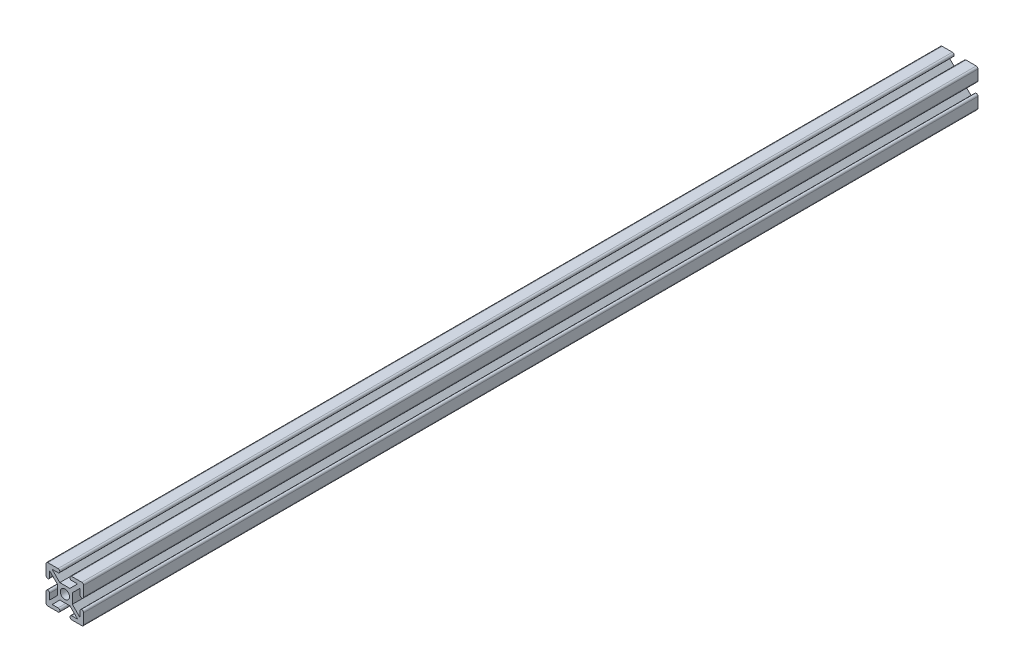
SolidWorks part; units mm, degrees
ref_plane "Front Plane" through (0, 0, 0) normal (0, 0, 1) x (1, 0, 0)
ref_plane "Top Plane" through (0, 0, 0) normal (0, 1, 0) x (1, 0, 0)
ref_plane "Right Plane" through (0, 0, 0) normal (1, 0, 0) x (0, 0, -1)
sketch "Sketch1" plane through (0, 0, 0) normal (0, 0, 1) x (1, 0, 0)
  line L0 (-19.949, 29.351) -> (-19.949, 30.776) construction
  line L1 (-0.8961, 13.201) -> (3.8289, 13.201)
  line L2 (-21.374, 38.926) -> (-21.374, 30.776)
  line L3 (-19.949, 40.351) -> (-11.799, 40.351)
  line L4 (-0.949, 40.351) -> (7.201, 40.351)
  line L5 (-16.4711, 13.201) -> (-11.7461, 13.201)
  line L6 (-12.374, 29.351) -> (-12.374, 21.351)
  line L7 (-21.3211, 19.926) -> (-21.3211, 11.776)
  line L8 (-19.9225, 10.3774) -> (-11.7461, 10.351)
  line L9 (8.626, 38.926) -> (8.626, 30.8797)
  line L10 (-18.524, 35.501) -> (-18.524, 30.776)
  line L11 (8.626, 20.0297) -> (8.626, 11.776)
  line L12 (-10.374, 38.926) -> (-11.799, 38.926) construction
  line L13 (-0.8961, 10.351) -> (7.201, 10.351)
  line L14 (-16.524, 37.501) -> (-11.799, 37.501)
  line L15 (-18.524, 19.926) -> (-18.524, 15.201)
  line L16 (-2.374, 38.926) -> (-0.949, 38.926) construction
  line L17 (-0.949, 37.501) -> (3.776, 37.501)
  line L18 (7.201, 29.4547) -> (7.201, 30.8797) construction
  line L19 (-10.374, 31.351) -> (-16.524, 37.501)
  line L20 (5.776, 35.501) -> (5.776, 30.8797)
  line L21 (7.201, 21.4547) -> (7.201, 20.0297) construction
  line L22 (-12.374, 29.351) -> (-18.524, 35.501)
  line L23 (5.776, 20.0297) -> (5.776, 15.201)
  line L24 (-2.3211, 11.776) -> (-0.8961, 11.776) construction
  line L25 (-12.374, 21.351) -> (-18.524, 15.201)
  line L26 (-10.374, 31.351) -> (-2.374, 31.351)
  line L27 (-2.374, 31.351) -> (3.776, 37.501)
  line L28 (-19.9225, 21.351) -> (-19.9225, 19.926) construction
  line L29 (-16.4711, 13.201) -> (-10.3211, 19.351)
  line L30 (-10.3211, 19.351) -> (-2.3211, 19.351)
  line L31 (-2.3211, 19.351) -> (3.8289, 13.201)
  line L32 (-10.3211, 11.776) -> (-11.7461, 11.776) construction
  line L33 (-0.374, 21.351) -> (5.776, 15.201)
  line L34 (-0.374, 29.351) -> (5.776, 35.501)
  line L35 (-0.374, 29.351) -> (-0.374, 21.351)
  circle A0 centre (-6.3211, 25.351) radius 3.645
  arc A1 (-21.374, 30.776) -> (-18.524, 30.776) centre (-19.949, 30.776) ccw
  arc A2 (-11.799, 37.501) -> (-11.799, 40.351) centre (-11.799, 38.926) ccw
  arc A3 (-0.949, 40.351) -> (-0.949, 37.501) centre (-0.949, 38.926) ccw
  arc A4 (5.776, 30.8797) -> (8.626, 30.8797) centre (7.201, 30.8797) ccw
  arc A5 (8.626, 20.0297) -> (5.776, 20.0297) centre (7.201, 20.0297) ccw
  arc A6 (-0.8961, 13.201) -> (-0.8961, 10.351) centre (-0.8961, 11.776) ccw
  arc A7 (-18.524, 19.926) -> (-21.3211, 19.926) centre (-19.9225, 19.926) ccw
  arc A8 (-11.7461, 10.351) -> (-11.7461, 13.201) centre (-11.7461, 11.776) ccw
  arc A9 (-21.3211, 11.776) -> (-19.9225, 10.3774) centre (-19.9225, 11.776) ccw
  arc A10 (7.201, 10.351) -> (8.626, 11.776) centre (7.201, 11.776) ccw
  arc A11 (8.626, 38.926) -> (7.201, 40.351) centre (7.201, 38.926) ccw
  arc A12 (-19.949, 40.351) -> (-21.374, 38.926) centre (-19.949, 38.926) ccw
  dimension "D1" = 1.425
  dimension "D2" = 1.425
  dimension "D3" = 1.425
  dimension "D4" = 1.425
  dimension "D5" = 1.425
  dimension "D6" = 1.425
  dimension "D7" = 1.425
extrude "Boss-Extrude1" add sketch "Sketch1" along normal blind 713.12
sketch "Sketch2" plane through (-0.374, 0, 0) normal (1, 0, 0) x (0, 0, -1)
  line L1 (-713.12, 21.351) -> (-713.12, 29.351) construction
  line L2 (-713.12, 30.8797) -> (-713.12, 38.926) construction
  circle A0 centre (-694.28, 25.351) radius 4
  point P4 (-713.12, 25.351)
  dimension "D1" = 8
  dimension "D2" = 0
  dimension "D3" = 18.84
extrude "Cut-Extrude1" cut sketch "Sketch2" against normal blind 30
sketch "Sketch3" plane through (-0.374, 0, 0) normal (1, 0, 0) x (0, 0, -1)
  circle A0 centre (-637.98, 25.351) radius 4
  arc A1 (-694.28, 29.351) -> (-694.28, 21.351) centre (-694.28, 25.351) ccw construction
  point P5 (-698.28, 25.351)
  dimension "D1" = 8
  dimension "D2" = 60.3
extrude "Cut-Extrude2" cut sketch "Sketch3" against normal blind 30
ref_plane "Plane1" through (-0.374, 21.351, 0) normal (0, 0, -1) x (-1, 0, 0)
sketch "Sketch5" plane through (-0.374, 0, 0) normal (1, 0, 0) x (0, 0, -1)
  line L0 (0, 21.351) -> (0, 29.351) construction
  line L1 (0, 30.8797) -> (0, 38.926) construction
  circle A0 centre (-18.84, 25.351) radius 4
  circle A1 centre (-75.14, 25.351) radius 4
  point P4 (0, 25.351)
  dimension "D1" = 8
  dimension "D4" = 8
  dimension "D2" = 0
  dimension "D3" = 18.84
  dimension "D5" = 56.3
extrude "Cut-Extrude3" cut sketch "Sketch5" against normal blind 30
